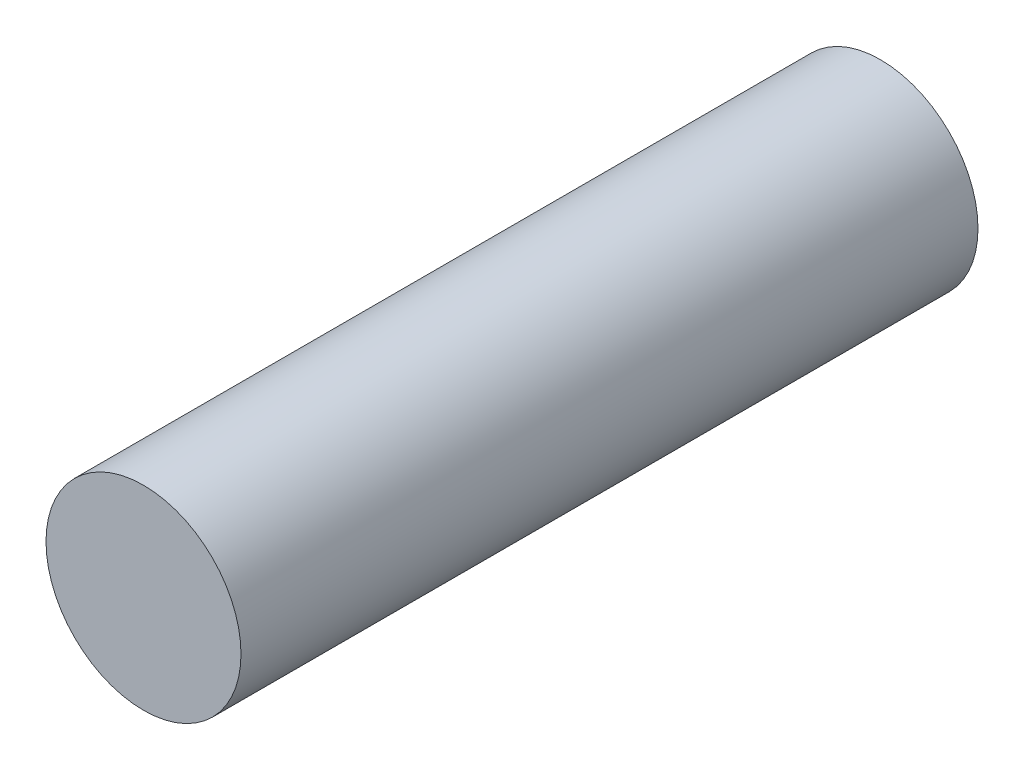
SolidWorks part; units mm, degrees
ref_plane "Alzado" through (0, 0, 0) normal (0, 0, 1) x (1, 0, 0)
ref_plane "Planta" through (0, 0, 0) normal (0, 1, 0) x (1, 0, 0)
ref_plane "Vista lateral" through (0, 0, 0) normal (1, 0, 0) x (0, 0, -1)
sketch "Croquis1" plane through (0, 0, 0) normal (0, 0, 1) x (1, 0, 0)
  circle A0 centre (0, 0) radius 3.175
  dimension "D1" = 6.35
extrude "Saliente-Extruir1" add sketch "Croquis1" along normal mid plane 24
